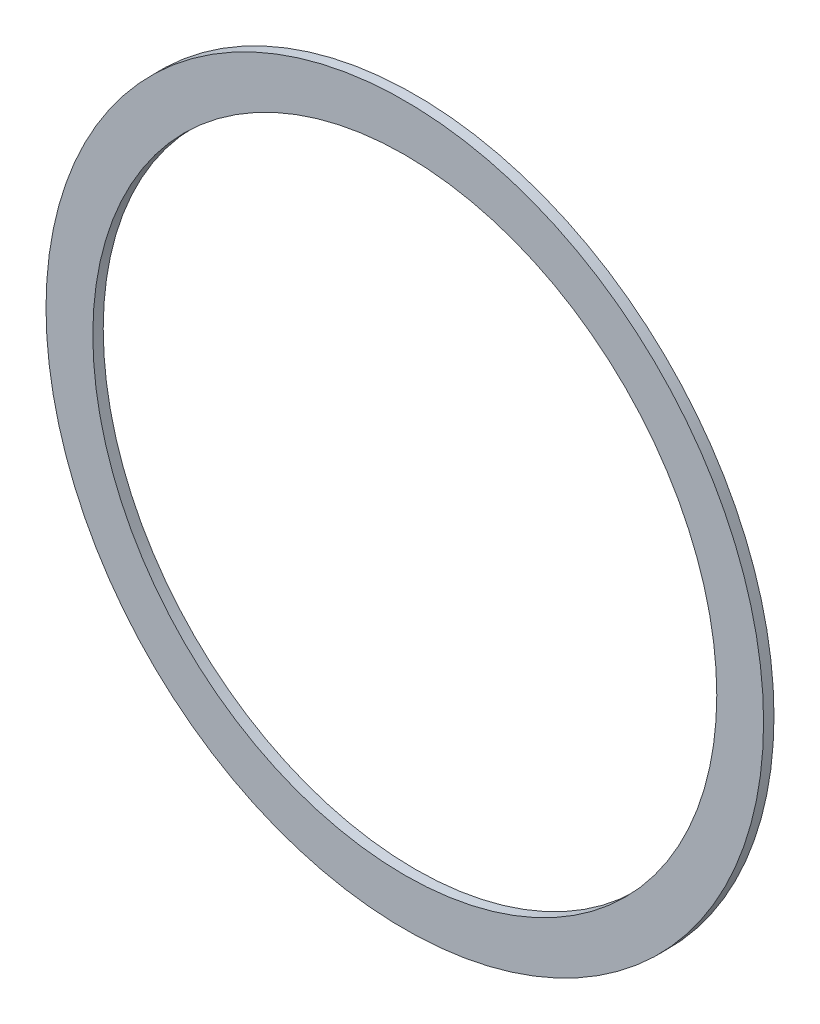
SolidWorks part; units mm, degrees
ref_plane "Front Plane" through (0, 0, 0) normal (0, 0, 1) x (1, 0, 0)
ref_plane "Top Plane" through (0, 0, 0) normal (0, 1, 0) x (1, 0, 0)
ref_plane "Right Plane" through (0, 0, 0) normal (1, 0, 0) x (0, 0, -1)
sketch "Sketch1" plane through (0, 0, 0) normal (0, 0, 1) x (1, 0, 0)
  circle A0 centre (0, 0) radius 69
  circle A1 centre (0, 0) radius 60
  dimension "D1" = 138
  dimension "D2" = 120
extrude "Boss-Extrude1" add sketch "Sketch1" along normal blind 2
